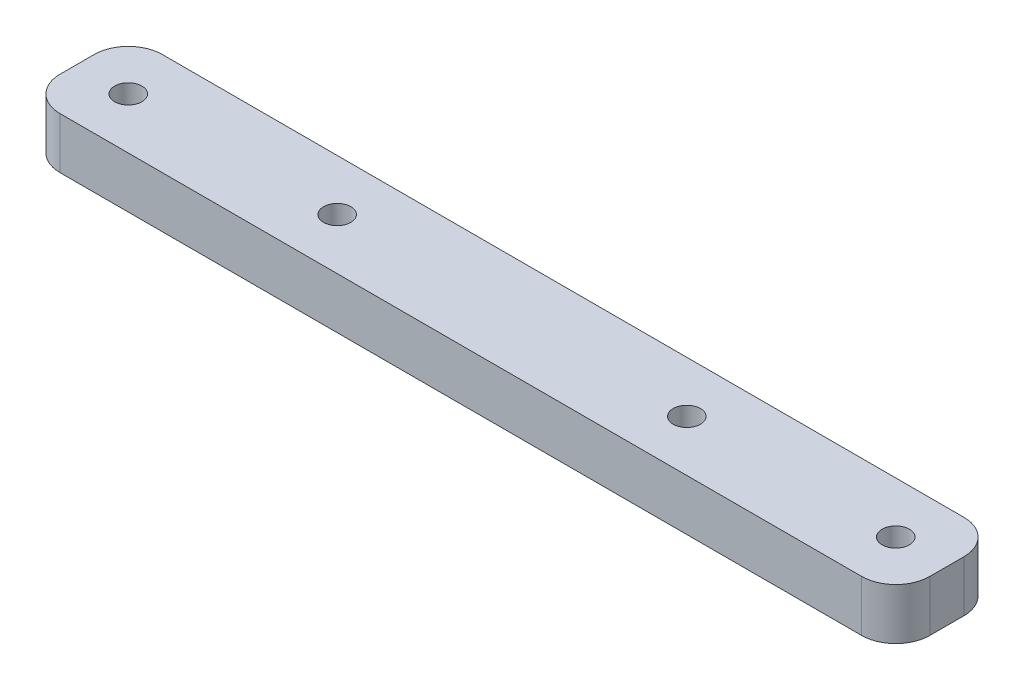
SolidWorks part; units mm, degrees
ref_plane "Front Plane" through (0, 0, 0) normal (0, 0, 1) x (1, 0, 0)
ref_plane "Top Plane" through (0, 0, 0) normal (0, 1, 0) x (1, 0, 0)
ref_plane "Right Plane" through (0, 0, 0) normal (1, 0, 0) x (0, 0, -1)
sketch "Sketch1" plane through (0, 0, 0) normal (0, 1, 0) x (1, 0, 0)
  line L0 (0, 6) -> (0, -6) construction
  line L5 (24.5, 0) -> (45, 0) construction
  line L6 (20.5, 0) -> (24.5, 0) construction
  line L7 (-51, 6) -> (51, 6)
  line L8 (-51, 6) -> (-51, -6)
  line L9 (-51, -6) -> (51, -6)
  line L10 (51, 6) -> (51, -6)
  line L11 (-20.5, 0) -> (-24.5, 0) construction
  line L12 (-24.5, 0) -> (-45, 0) construction
  circle A2 centre (-45, 0) radius 1.6
  circle A3 centre (-20.5, 0) radius 1.6
  circle A6 centre (20.5, 0) radius 1.6
  circle A7 centre (45, 0) radius 1.6
  dimension "D3" = 3.2
  dimension "D4" = 90
  dimension "D1" = 20.5
  dimension "D2" = 4
  dimension "D5" = 6
  dimension "D6" = 12
extrude "Boss-Extrude1" add sketch "Sketch1" along normal mid plane 6
fillet "Fillet1" radius 4 4 edges at (-51, 0, -6) (51, 0, 6) (51, 0, -6) (-51, 0, 6)
